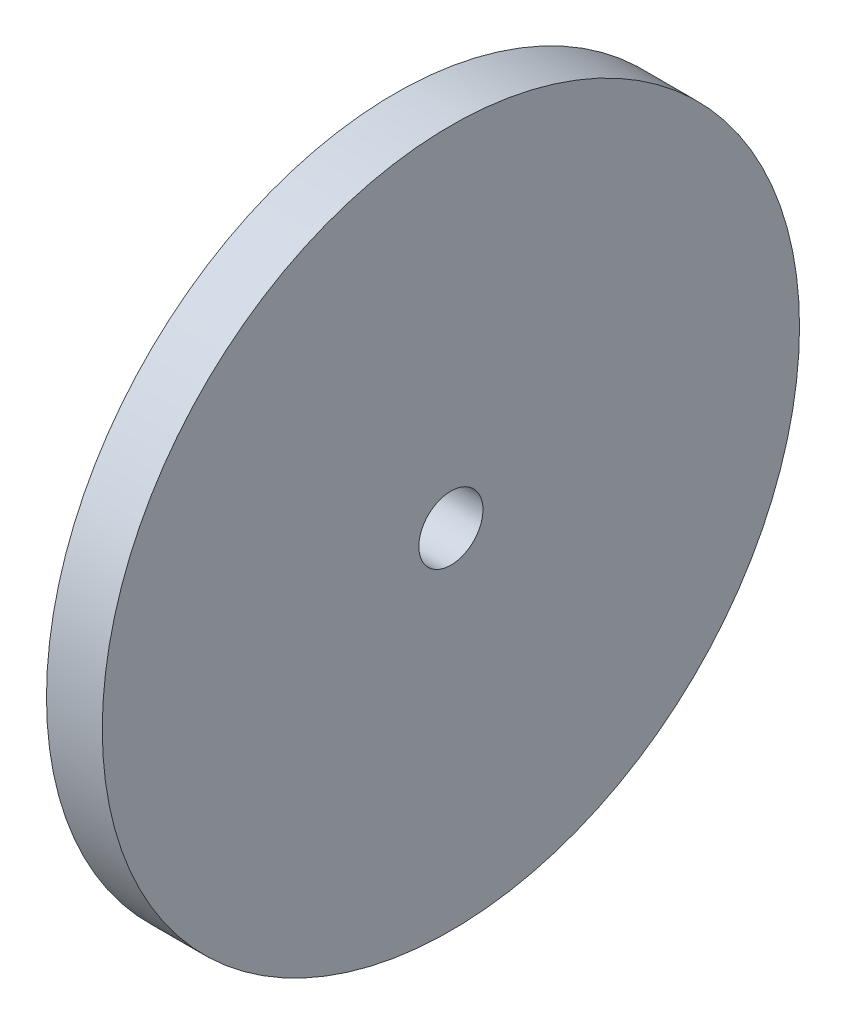
SolidWorks part; units mm, degrees
ref_plane "Front Plane" through (0, 0, 0) normal (1, 0, 0) x (0, 1, 0)
ref_plane "Top Plane" through (0, 0, 0) normal (0, 0, 1) x (0, 1, 0)
ref_plane "Right Plane" through (0, 0, 0) normal (0, 1, 0) x (-1, 0, 0)
sketch "Sketch1" plane through (0, 0, 0) normal (1, 0, 0) x (0, 1, 0)
  circle A0 centre (0, 0) radius 15.875
  circle A1 centre (0, 0) radius 1.4605
  dimension "D1" = 2.921
  dimension "D2" = 31.75
extrude "Boss-Extrude1" add sketch "Sketch1" along normal blind 2.54
